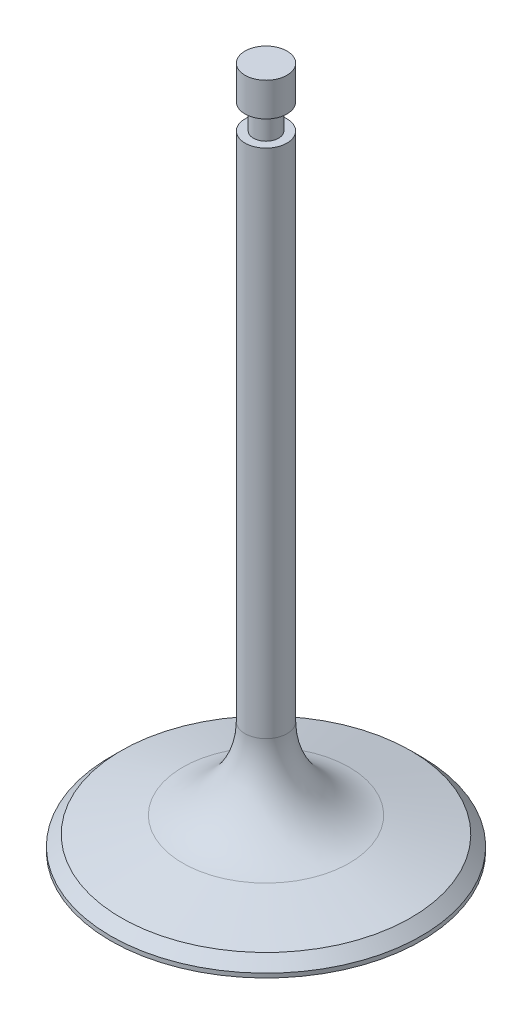
SolidWorks part; units mm, degrees
ref_plane "Plano frontal" through (0, 0, 0) normal (0, 0, 1) x (1, 0, 0)
ref_plane "Plano superior" through (0, 0, 0) normal (0, 1, 0) x (1, 0, 0)
ref_plane "Plano direito" through (0, 0, 0) normal (1, 0, 0) x (0, 0, -1)
sketch "Sketch1" plane through (0, 0, 0) normal (1, 0, 0) x (0, 0, -1)
  line L0 (0, 0) -> (0, 82.79)
  line L1 (0, 82.79) -> (2.5, 82.79)
  line L2 (2.5, 82.79) -> (2.5, 78.79)
  line L3 (2.5, 78.79) -> (1.5, 78.79)
  line L4 (1.5, 78.79) -> (1.5, 75.79)
  line L5 (1.5, 75.79) -> (2.5, 75.79)
  line L6 (2.5, 75.79) -> (2.5, 14.8755)
  line L7 (9.9118, 5.2163) -> (17.25, 3.25)
  line L8 (17.25, 3.25) -> (18.5, 2)
  line L9 (18.5, 2) -> (18.5, 1.5)
  line L10 (0, 0) -> (-10.2094, 0) construction
  line L11 (18.5, 2) -> (11.0342, 2) construction
  arc A0 (2.5, 14.8755) -> (9.9118, 5.2163) centre (12.5, 14.8755) ccw
  arc A1 (0, 0) -> (18.5, 1.5) centre (0, 114.8333) ccw
  point P15 (2, 78.79)
  dimension "D12" = 10
  dimension "D1" = 18.5
  dimension "D2" = 1.5
  dimension "D3" = 0.5
  dimension "D4" = 1.25
  dimension "D5" = 15
  dimension "D6" = 45
  dimension "D7" = 2.5
  dimension "D8" = 3
  dimension "D9" = 1
  dimension "D10" = 4
  dimension "D11" = 82.79
revolve "Revolve1" add sketch "Sketch1" angle 360 about L0
